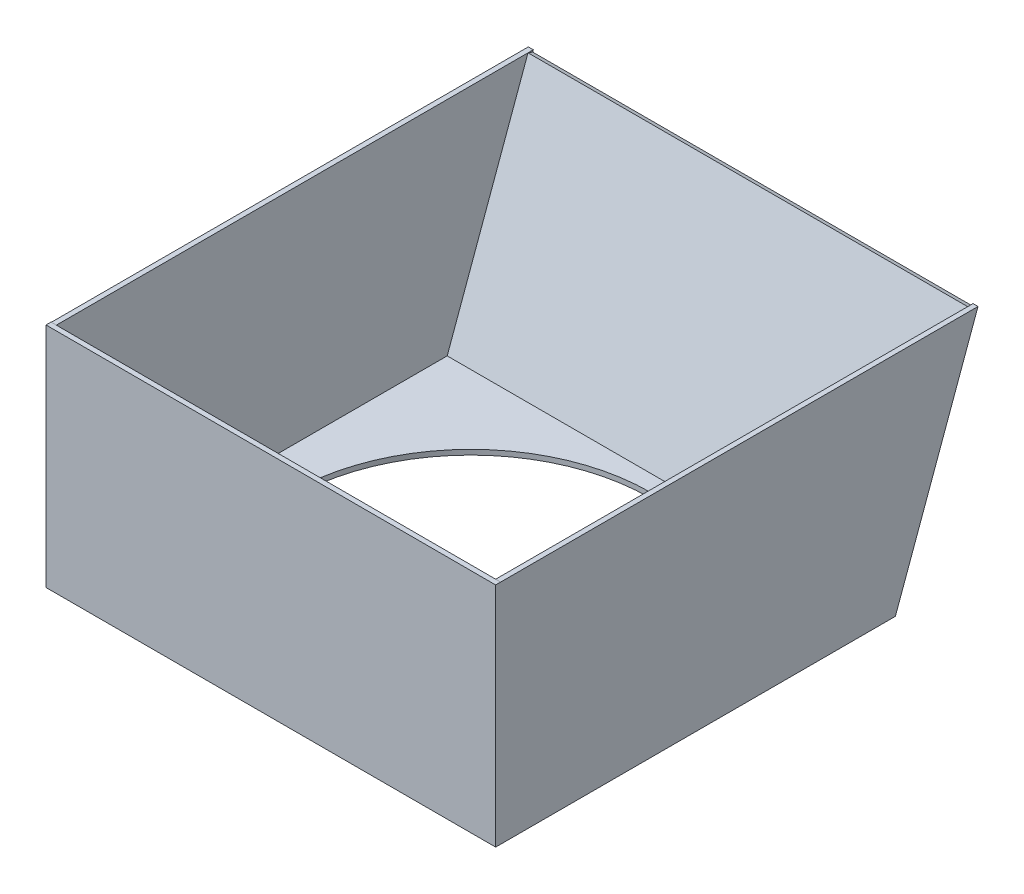
SolidWorks part; units mm, degrees
ref_plane "前视基准面" through (0, 0, 0) normal (0, 0, 1) x (1, 0, 0)
ref_plane "上视基准面" through (0, 0, 0) normal (0, 1, 0) x (1, 0, 0)
ref_plane "右视基准面" through (0, 0, 0) normal (1, 0, 0) x (0, 0, -1)
other "Configuration Table"
sketch "草图1" plane through (0, 0, 0) normal (0, 1, 0) x (1, 0, 0)
  line L1 (-112.5, 100) -> (112.5, 100)
  line L2 (-112.5, 100) -> (-112.5, -100)
  line L3 (-112.5, -100) -> (112.5, -100)
  line L4 (112.5, 100) -> (112.5, -100)
  line L5 (-112.5, 100) -> (112.5, -100) construction
  line L6 (-112.5, -100) -> (112.5, 100) construction
  circle A0 centre (0, 0) radius 90
  point P0 (0, 0)
  dimension "D1" = 200
  dimension "D2" = 225
extrude "凸台-拉伸1" add sketch "草图1" along normal blind 2.5
sketch "草图8" plane through (0, 0, 0) normal (1, 0, 0) x (0, 0, -1)
  line L0 (77.8788, 0) -> (100, 0)
  line L1 (-100, 0) -> (100, 0) construction
  line L2 (100, 0) -> (141.0424, 112.7631)
ref_plane "基准面7" through (0, -32.1394, -88.3022) normal (0, 0.342, 0.9397) x (1, 0, 0)
sketch "草图9" plane through (0, -32.1394, -88.3022) normal (0, 0.342, 0.9397) x (1, 0, 0)
  line L0 (112.5, 34.202) -> (-112.5, 34.202)
  line L1 (-112.5, 34.202) -> (-112.5, 154.202)
  line L2 (-112.5, 154.202) -> (112.5, 154.202)
  line L3 (112.5, 154.202) -> (112.5, 34.202)
extrude "凸台-拉伸11" add sketch "草图9" along normal blind 2.5
ref_plane "基准面8" through (0, 112, 0) normal (0, 1, 0) x (1, 0, 0)
ref_plane "基准面9" through (-112.5, 0, 0) normal (-1, 0, 0) x (0, 0, 1)
sketch "草图12" plane through (-112.5, 0, 0) normal (-1, 0, 0) x (0, 0, 1)
  line L0 (-100, 0) -> (-141.3536, 113.6182)
  line L1 (-67.1397, -90.2829) -> (-109.4647, 26.0041) construction
  line L2 (-141.3536, 113.6182) -> (100, 113.6182)
  line L3 (100, 113.6182) -> (100, 0)
  line L4 (100, 0) -> (-100, 0)
extrude "凸台-拉伸12" add sketch "草图12" against normal blind 2.5
ref_plane "基准面10" through (112.5, 0, 0) normal (1, 0, 0) x (0, 0, -1)
sketch "草图13" plane through (112.5, 0, 0) normal (1, 0, 0) x (0, 0, -1)
  line L0 (100, 0) -> (141.3536, 113.6182)
  line L1 (109.4647, 26.0041) -> (67.1397, -90.2829) construction
  line L2 (138.6932, 113.6182) -> (141.3536, 113.6182) construction
  line L3 (141.3536, 113.6182) -> (-100, 113.6182)
  line L4 (-100, 113.6182) -> (-100, 0)
  line L5 (-100, 0) -> (100, 0)
extrude "凸台-拉伸13" add sketch "草图13" against normal blind 2.5
ref_plane "基准面11" through (0, 0, 100) normal (0, 0, 1) x (1, 0, 0)
sketch "草图15" plane through (0, 0, 100) normal (0, 0, 1) x (1, 0, 0)
  line L0 (-112.5, 0) -> (-112.5, 113.7915)
  line L1 (-112.5, 62.5853) -> (-112.5, -62.5853) construction
  line L2 (-112.5, 113.7915) -> (112.5, 113.6182)
  line L3 (112.5, 113.6182) -> (112.5, 0)
  line L4 (112.5, 0) -> (-112.5, 0)
extrude "凸台-拉伸14" add sketch "草图15" against normal blind 2.5
